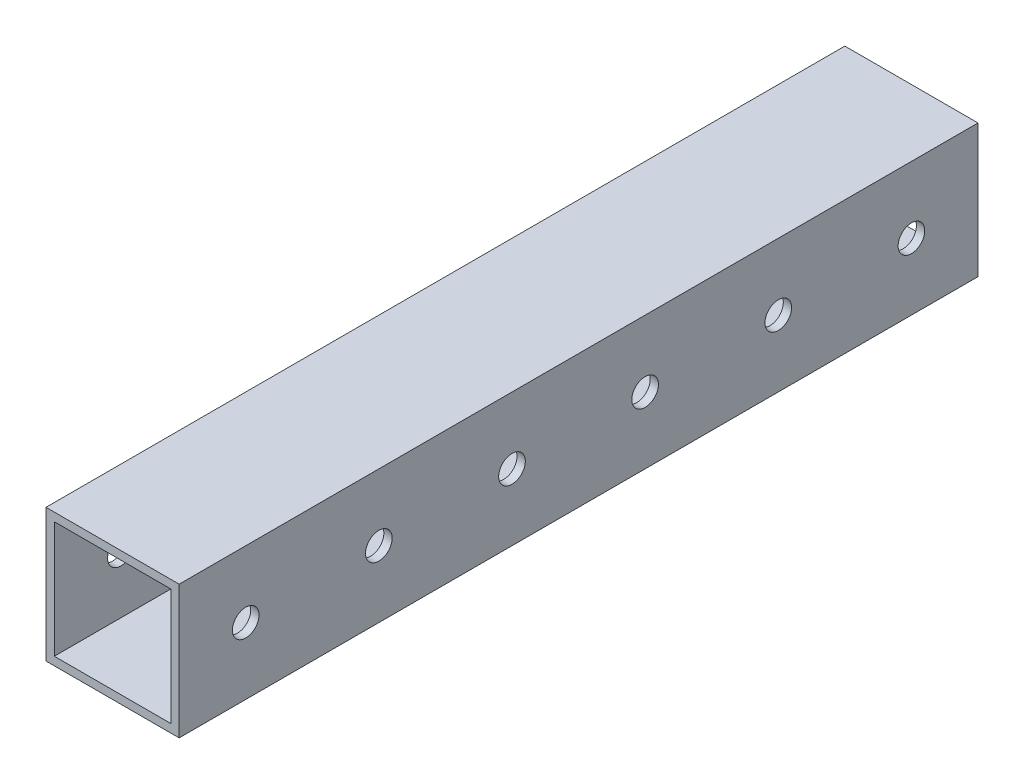
SolidWorks part; units mm, degrees
ref_plane "Front Plane" through (0, 0, 0) normal (0, 0, 1) x (1, 0, 0)
ref_plane "Top Plane" through (0, 0, 0) normal (0, 1, 0) x (1, 0, 0)
ref_plane "Right Plane" through (0, 0, 0) normal (1, 0, 0) x (0, 0, -1)
sketch "Sketch1" plane through (0, 0, 0) normal (0, 0, 1) x (1, 0, 0)
  line L1 (0, 0) -> (25.4, 0)
  line L2 (0, 0) -> (0, 25.4)
  line L3 (0, 25.4) -> (25.4, 25.4)
  line L4 (25.4, 0) -> (25.4, 25.4)
  line L5 (1.5875, 1.5875) -> (23.8125, 1.5875)
  line L6 (1.5875, 1.5875) -> (1.5875, 23.8125)
  line L7 (1.5875, 23.8125) -> (23.8125, 23.8125)
  line L8 (23.8125, 1.5875) -> (23.8125, 23.8125)
  dimension "D1" = 25.4
  dimension "D2" = 1.5875
  dimension "D3" = 1.5875
  dimension "D4" = 1.5875
  dimension "D5" = 1.5875
extrude "Boss-Extrude1" add sketch "Sketch1" along normal blind 152.4
sketch "Sketch4" plane through (25.4, 0, 0) normal (1, 0, 0) x (0, 0, -1)
  line L0 (-152.4, 25.4) -> (0, 25.4) construction
  line L1 (-152.4, 0) -> (-152.4, 25.4) construction
  line L2 (-76.2, 25.4) -> (-76.2, 0) construction
  line L3 (-152.4, 0) -> (0, 0) construction
  circle A0 centre (-139.7, 12.7) radius 2.54
  circle A14 centre (-114.3, 12.7) radius 2.54
  circle A15 centre (-88.9, 12.7) radius 2.54
  circle A16 centre (-63.5, 12.7) radius 2.54
  circle A17 centre (-38.1, 12.7) radius 2.54
  circle A18 centre (-12.7, 12.7) radius 2.54
  dimension "D1" = 5.08
  dimension "D2" = 12.7
  dimension "D3" = 12.7
  dimension "D4" = 3
extrude "Cut-Extrude3" cut sketch "Sketch4" against normal through all
